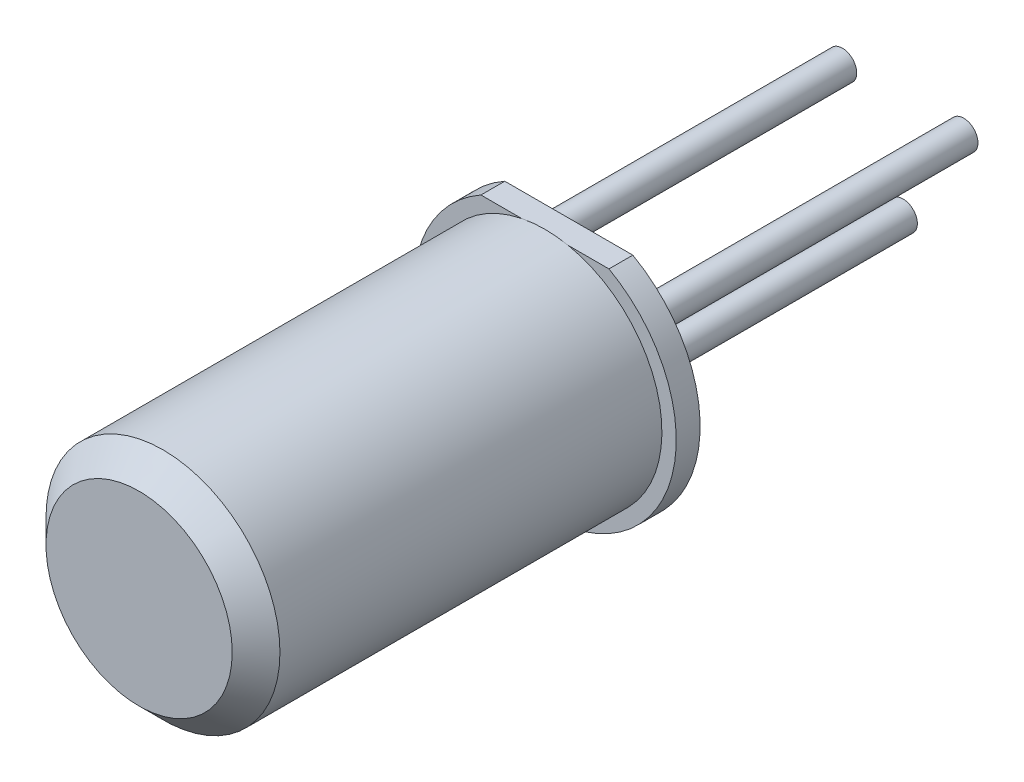
SolidWorks part; units mm, degrees
ref_plane "Спереди" through (0, 0, 0) normal (0, 0, 1) x (1, 0, 0)
ref_plane "Сверху" through (0, 0, 0) normal (0, 1, 0) x (1, 0, 0)
ref_plane "Справа" through (0, 0, 0) normal (1, 0, 0) x (0, 0, -1)
sketch "Эскиз1" plane through (0, 0, 0) normal (0, 0, 1) x (1, 0, 0)
  line L0 (0, -0.7919) -> (0, 1.8966) construction
  line L5 (0, 0) -> (0.6495, 0) construction
  circle A0 centre (-1.27, 1.05) radius 0.3
  circle A1 centre (1.27, 1.05) radius 0.3
  circle A2 centre (0, -1.05) radius 0.3
  dimension "D1" = 0.6
  dimension "D4" = 1.05
  dimension "D2" = 2.54
  dimension "D3" = 2.1
extrude "Вытянуть5" add sketch "Эскиз1" along normal blind 7
sketch "Эскиз5" plane through (0, 0, 7) normal (0, 0, 1) x (1, 0, 0)
  line L0 (0, 0) -> (0, 4.5352) construction
  line L1 (-1.3408, 2.401) -> (1.3408, 2.401)
  arc A0 (-1.3408, 2.401) -> (1.3408, 2.401) centre (0, 0) ccw
extrude "Вытянуть6" add sketch "Эскиз5" along normal blind 0.5
sketch "Эскиз6" plane through (0, 0, 7.5) normal (0, 0, 1) x (1, 0, 0)
  circle A0 centre (0, 0) radius 2.45
  arc A1 (-1.3408, 2.401) -> (1.3408, 2.401) centre (0, 0) ccw construction
extrude "Вытянуть7" add sketch "Эскиз6" along normal blind 8.5
chamfer "Фаска1" distance 0.5 angle 45 1 edges at (2.45, 0, 16)
